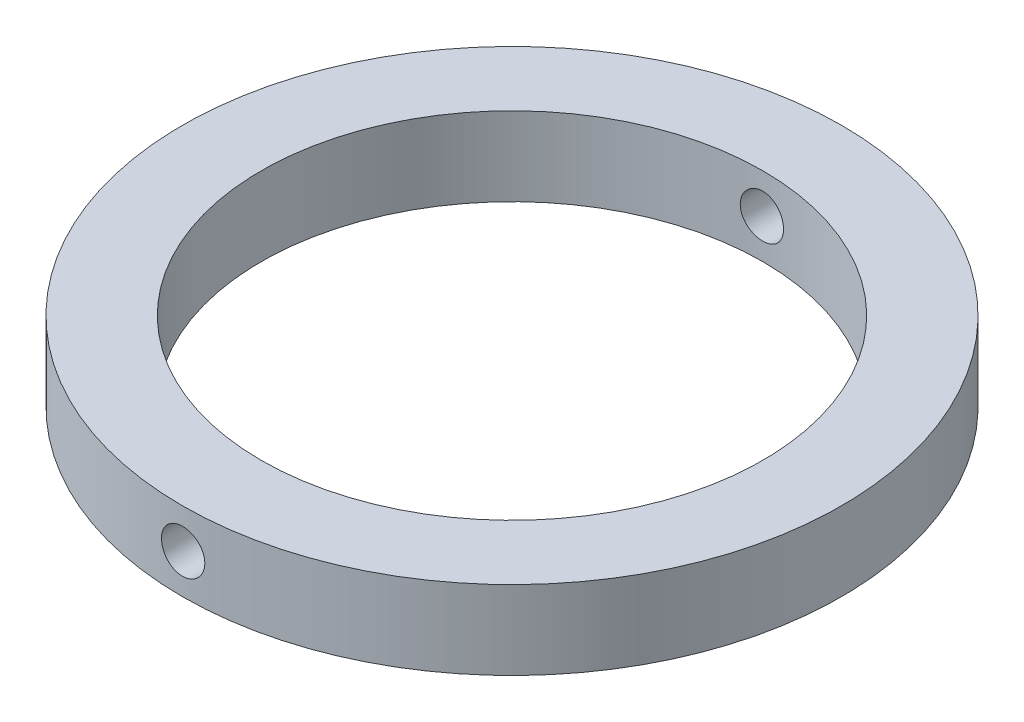
SolidWorks part; units mm, degrees
ref_plane "Front Plane" through (0, 0, 0) normal (0, 0, 1) x (1, 0, 0)
ref_plane "Top Plane" through (0, 0, 0) normal (0, 1, 0) x (1, 0, 0)
ref_plane "Right Plane" through (0, 0, 0) normal (1, 0, 0) x (0, 0, -1)
sketch "Sketch1" plane through (0, 0, 0) normal (0, 1, 0) x (1, 0, 0)
  circle A0 centre (0, 0) radius 41.85
  circle A1 centre (0, 0) radius 31.85
  dimension "D1" = 83.7
  dimension "D2" = 63.7
extrude "Boss-Extrude1" add sketch "Sketch1" along normal blind 10
sketch "Sketch5" plane through (0, 0, 0) normal (0, 0, 1) x (1, 0, 0)
  line L0 (41.85, 10) -> (-41.85, 10) construction
  circle A0 centre (0, 5) radius 2.75
  point P4 (0, 0)
  dimension "D1" = 5.5
  dimension "D2" = 5
extrude "Cut-Extrude1" cut sketch "Sketch5" along normal through all both and the other way through all
